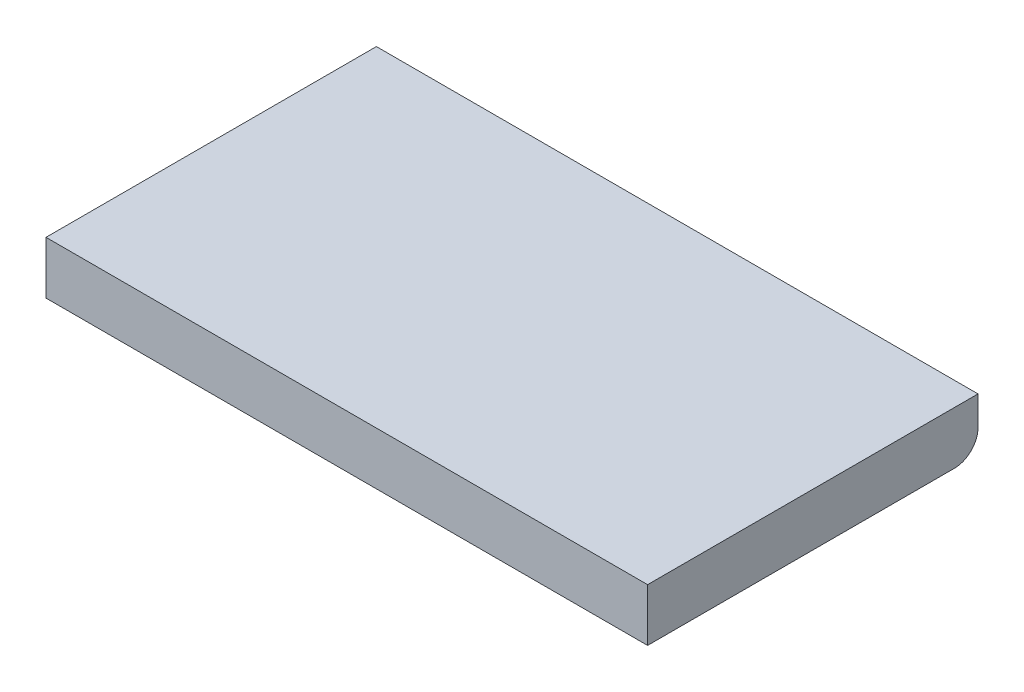
SolidWorks part; units mm, degrees
ref_plane "Front Plane" through (0, 0, 0) normal (0, 0, 1) x (1, 0, 0)
ref_plane "Top Plane" through (0, 0, 0) normal (0, 1, 0) x (1, 0, 0)
ref_plane "Right Plane" through (0, 0, 0) normal (1, 0, 0) x (0, 0, -1)
sketch "Sketch2" plane through (0, 0, 0) normal (0, 1, 0) x (1, 0, 0)
  line L1 (-326.517, -179.324) -> (326.517, -179.324)
  line L2 (-326.517, -179.324) -> (-326.517, 179.324)
  line L3 (-326.517, 179.324) -> (326.517, 179.324)
  line L4 (326.517, -179.324) -> (326.517, 179.324)
  line L5 (-326.517, -179.324) -> (326.517, 179.324) construction
  line L6 (-326.517, 179.324) -> (326.517, -179.324) construction
  point P0 (0, 0)
  dimension "D1" = 653.034
  dimension "D2" = 358.648
extrude "Boss-Extrude1" add sketch "Sketch2" along normal blind 57.15
sketch "Sketch3" plane through (0, 0, -179.324) normal (0, 0, -1) x (-1, 0, 0)
  line L0 (-263.017, 0) -> (263.017, 0)
  line L1 (-326.517, 0) -> (326.517, 0) construction
  line L2 (-263.017, 0) -> (-263.017, 31.75)
  line L3 (-263.017, 31.75) -> (263.017, 31.75)
  line L4 (263.017, 31.75) -> (263.017, 0)
  point P6 (0, 0)
  dimension "D1" = 526.034
  dimension "D2" = 31.75
extrude "Cut-Extrude1" cut sketch "Sketch3" against normal blind 25.4
sketch "Sketch4" plane through (263.017, 0, 0) normal (-1, 0, 0) x (0, 0, 1)
  circle A0 centre (-165.5853, 17.1438) radius 9.525
  dimension "D1" = 19.05
extrude "Boss-Extrude2" add sketch "Sketch4" along normal blind 25.4
ref_plane "Plane1" through (0, 0, 0) normal (-1, 0, 0) x (0, 0, 1)
mirror "Mirror1" about plane through (0, 0, 0) normal (-1, 0, 0) of "Boss-Extrude2"
fillet "Fillet1" radius 25.4 2 edges at (-294.767, 0, -179.324) (294.767, 0, -179.324)
